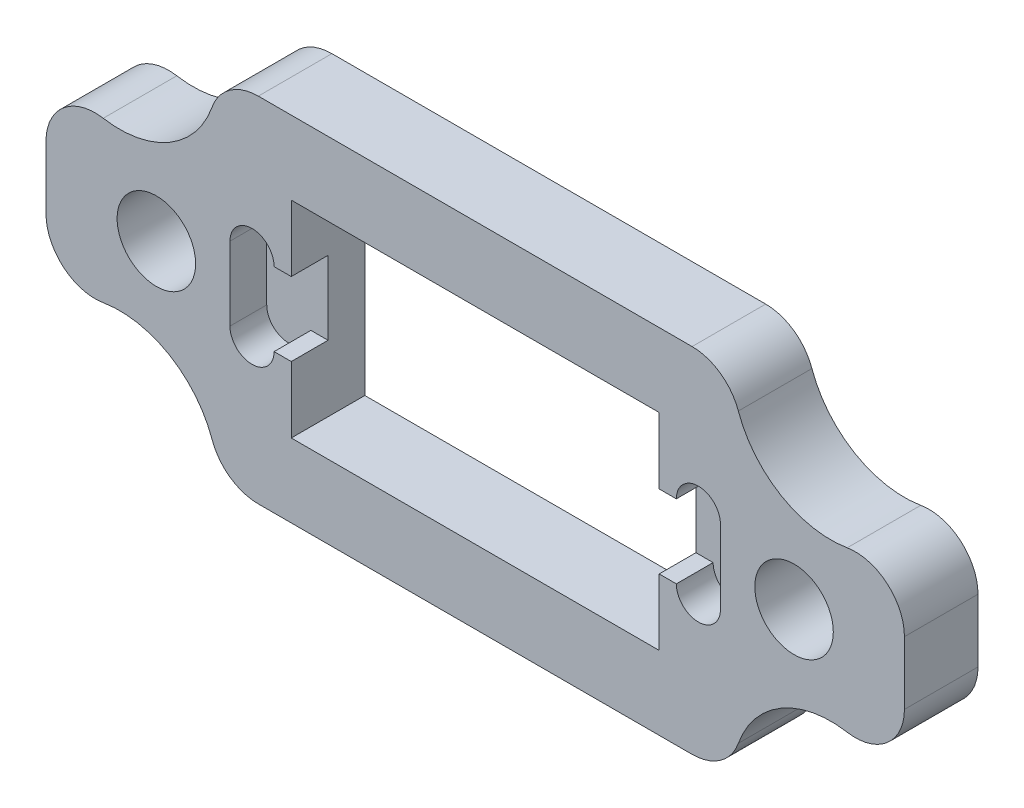
SolidWorks part; units mm, degrees
material "Thornel Mat VMA"
ref_plane "前视基准面" through (0, 0, 0) normal (0, 0, 1) x (1, 0, 0)
ref_plane "上视基准面" through (0, 0, 0) normal (0, 1, 0) x (1, 0, 0)
ref_plane "右视基准面" through (0, 0, 0) normal (1, 0, 0) x (0, 0, -1)
sketch "草图1" plane through (0, 0, 0) normal (0, 0, 1) x (1, 0, 0)
  line L1 (-7.5, -4.2) -> (7.5, -4.2)
  line L2 (-7.5, -4.2) -> (-7.5, 4.2)
  line L3 (-7.5, 4.2) -> (7.5, 4.2)
  line L4 (7.5, -4.2) -> (7.5, 4.2)
  line L5 (-7.5, -4.2) -> (7.5, 4.2) construction
  line L6 (-7.5, 4.2) -> (7.5, -4.2) construction
  line L7 (-17.5, -7.2) -> (17.5, -7.2)
  line L8 (-17.5, -7.2) -> (-17.5, 7.2)
  line L9 (-17.5, 7.2) -> (17.5, 7.2)
  line L10 (17.5, -7.2) -> (17.5, 7.2)
  line L11 (-17.5, -7.2) -> (17.5, 7.2) construction
  line L12 (-17.5, 7.2) -> (17.5, -7.2) construction
  point P0 (0, 0)
  point P6 (0, 0)
  dimension "D1" = 8.4
  dimension "D2" = 15
  dimension "D3" = 3
  dimension "D4" = 10
extrude "凸台-拉伸1" add sketch "草图1" along normal blind 3
sketch "草图2" plane through (0, 0, 3) normal (0, 0, 1) x (1, 0, 0)
  line L1 (-10, -1.5) -> (10, -1.5)
  line L2 (-10, -1.5) -> (-10, 1.5)
  line L3 (-10, 1.5) -> (10, 1.5)
  line L4 (10, -1.5) -> (10, 1.5)
  line L5 (-10, -1.5) -> (10, 1.5) construction
  line L6 (-10, 1.5) -> (10, -1.5) construction
  point P0 (0, 0)
  dimension "D1" = 20
  dimension "D2" = 3
extrude "切除-拉伸1" cut sketch "草图2" against normal blind 1.5
sketch "草图3" plane through (0, 0, 3) normal (0, 0, 1) x (1, 0, 0)
  line L0 (-17.5, 0) -> (17.5, 0) construction
  line L1 (-17.5, 7.2) -> (-17.5, -7.2) construction
  line L2 (17.5, -7.2) -> (17.5, 7.2) construction
  circle A0 centre (-13, 0) radius 1.6
  circle A1 centre (13, 0) radius 1.6
  dimension "D1" = 13
  dimension "D2" = 3.2
  dimension "D3" = 13
  dimension "D4" = 3.2
extrude "切除-拉伸2" cut sketch "草图3" against normal blind 20
sketch "草图5" plane through (0, 0, 3) normal (0, 0, 1) x (1, 0, 0)
  line L0 (17.5, 7.2) -> (-17.5, 7.2) construction
  line L1 (-17.5, 7.2) -> (-17.5, -7.2) construction
  line L2 (0, 7.2) -> (0, -7.2) construction
  line L3 (-17.5, -7.2) -> (17.5, -7.2) construction
  line L4 (-17.5, 0) -> (17.5, 0) construction
  line L5 (17.5, -7.2) -> (17.5, 7.2) construction
  circle A0 centre (-14.5, 7.2) radius 4
  circle A1 centre (14.5, 7.2) radius 4
  circle A2 centre (14.5, -7.2) radius 4
  circle A3 centre (-14.5, -7.2) radius 4
  dimension "D1" = 3
  dimension "D2" = 8
extrude "切除-拉伸4" cut sketch "草图5" against normal blind 10
fillet "圆角2" radius 2 8 edges at (-10.5, -7.2, 1.5) (10.5, -7.2, 1.5) (17.5, -4.5542, 1.5) (17.5, 4.5542, 1.5) (10.5, 7.2, 1.5) (-17.5, 4.5542, 1.5) (-17.5, -4.5542, 1.5) (-10.5, 7.2, 1.5)
sketch "草图6" plane through (0, 0, 3) normal (0, 0, 1) x (1, 0, 0)
  line L0 (-7.5, 1.5) -> (-10, 1.5) construction
  line L1 (-10, -1.5) -> (-7.5, -1.5) construction
  line L2 (10, 1.5) -> (7.5, 1.5) construction
  line L3 (7.5, -1.5) -> (10, -1.5) construction
  circle A0 centre (-9.1, 1.5) radius 0.9
  circle A1 centre (-9.1, -1.5) radius 0.9
  circle A2 centre (9.1, 1.5) radius 0.9
  circle A3 centre (9.1, -1.5) radius 0.9
  dimension "D1" = 1.8
extrude "切除-拉伸5" cut sketch "草图6" against normal blind 1.5
